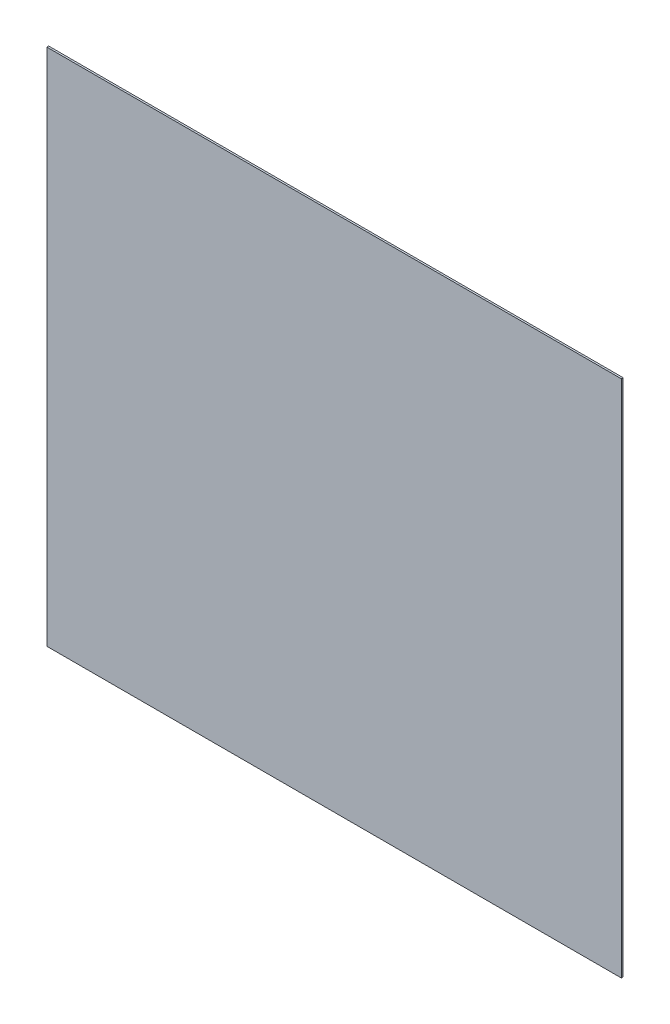
SolidWorks part; units mm, degrees
ref_plane "Front Plane" through (0, 0, 0) normal (0, 0, 1) x (1, 0, 0)
ref_plane "Top Plane" through (0, 0, 0) normal (0, 1, 0) x (1, 0, 0)
ref_plane "Right Plane" through (0, 0, 0) normal (1, 0, 0) x (0, 0, -1)
sketch "Sketch1" plane through (0, 0, 0) normal (0, 0, 1) x (1, 0, 0)
  line L1 (0, 0) -> (787.4, 0)
  line L2 (0, 0) -> (0, 711.2)
  line L3 (0, 711.2) -> (787.4, 711.2)
  line L4 (787.4, 0) -> (787.4, 711.2)
  dimension "D1" = 711.2
  dimension "D2" = 787.4
extrude "Boss-Extrude1" add sketch "Sketch1" along normal blind 2.54
